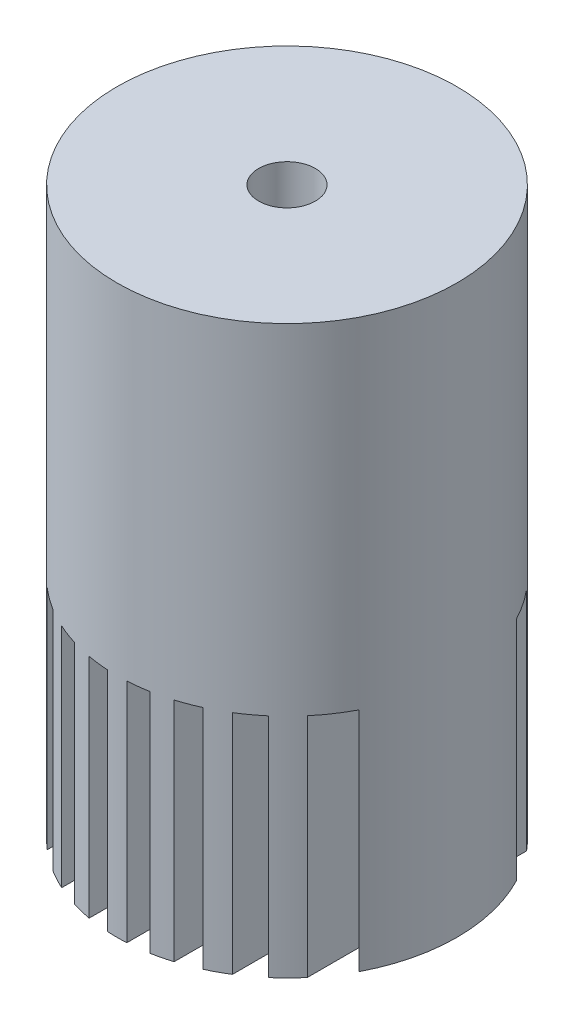
SolidWorks part; units mm, degrees
ref_plane "Plan de face" through (0, 0, 0) normal (0, 0, 1) x (1, 0, 0)
ref_plane "Plan de dessus" through (0, 0, 0) normal (0, 1, 0) x (1, 0, 0)
ref_plane "Plan de droite" through (0, 0, 0) normal (1, 0, 0) x (0, 0, -1)
sketch "Esquisse1" plane through (0, 0, 0) normal (0, 1, 0) x (1, 0, 0)
  circle A0 centre (0, 0) radius 38.1
extrude "Boss.-Extru.1" add sketch "Esquisse1" along normal mid plane 127
sketch "Esquisse2" plane through (0, 63.5, 0) normal (0, 1, 0) x (1, 0, 0)
  circle A0 centre (0, 0) radius 6.35
extrude "Enlèv. mat.-Extru.1" cut sketch "Esquisse2" against normal blind 17.78
sketch "Esquisse3" plane through (0, 45.72, 0) normal (0, 1, 0) x (1, 0, 0)
  circle A0 centre (0, 0) radius 25.4
extrude "Enlèv. mat.-Extru.2" cut sketch "Esquisse3" against normal blind 50.8
sketch "Esquisse4" plane through (0, -63.5, 0) normal (0, -1, 0) x (1, 0, 0)
  line L36 (24.792, -38.1) -> (24.792, 38.1)
  line L37 (33.782, -38.1) -> (29.1147, -38.1)
  line L38 (33.782, -38.1) -> (33.782, 38.1)
  line L39 (33.782, 38.1) -> (29.1147, 38.1)
  line L40 (29.1147, -38.1) -> (29.1147, 38.1)
  line L41 (24.792, -38.1) -> (20.1247, -38.1)
  line L42 (20.1247, -38.1) -> (20.1247, 38.1)
  line L43 (24.792, 38.1) -> (20.1247, 38.1)
  line L44 (15.802, -38.1) -> (15.802, 38.1)
  line L45 (15.802, -38.1) -> (11.1347, -38.1)
  line L46 (11.1347, -38.1) -> (11.1347, 38.1)
  line L47 (15.802, 38.1) -> (11.1347, 38.1)
  line L48 (6.812, -38.1) -> (6.812, 38.1)
  line L49 (6.812, -38.1) -> (2.1447, -38.1)
  line L50 (2.1447, -38.1) -> (2.1447, 38.1)
  line L51 (6.812, 38.1) -> (2.1447, 38.1)
  line L52 (-2.178, -38.1) -> (-2.178, 38.1)
  line L53 (-2.178, -38.1) -> (-6.8453, -38.1)
  line L54 (-6.8453, -38.1) -> (-6.8453, 38.1)
  line L55 (-2.178, 38.1) -> (-6.8453, 38.1)
  line L56 (-11.168, -38.1) -> (-11.168, 38.1)
  line L57 (-11.168, -38.1) -> (-15.8352, -38.1)
  line L58 (-15.8352, -38.1) -> (-15.8352, 38.1)
  line L59 (-11.168, 38.1) -> (-15.8352, 38.1)
  line L60 (-20.158, -38.1) -> (-20.158, 38.1)
  line L61 (-20.158, -38.1) -> (-24.8253, -38.1)
  line L62 (-24.8253, -38.1) -> (-24.8253, 38.1)
  line L63 (-20.158, 38.1) -> (-24.8253, 38.1)
  line L64 (-29.148, -38.1) -> (-29.148, 38.1)
  line L65 (-29.148, -38.1) -> (-33.8153, -38.1)
  line L66 (-33.8153, -38.1) -> (-33.8153, 38.1)
  line L67 (-29.148, 38.1) -> (-33.8153, 38.1)
  dimension "D1" = 8
extrude "Enlèv. mat.-Extru.3" cut sketch "Esquisse4" against normal blind 50.8
